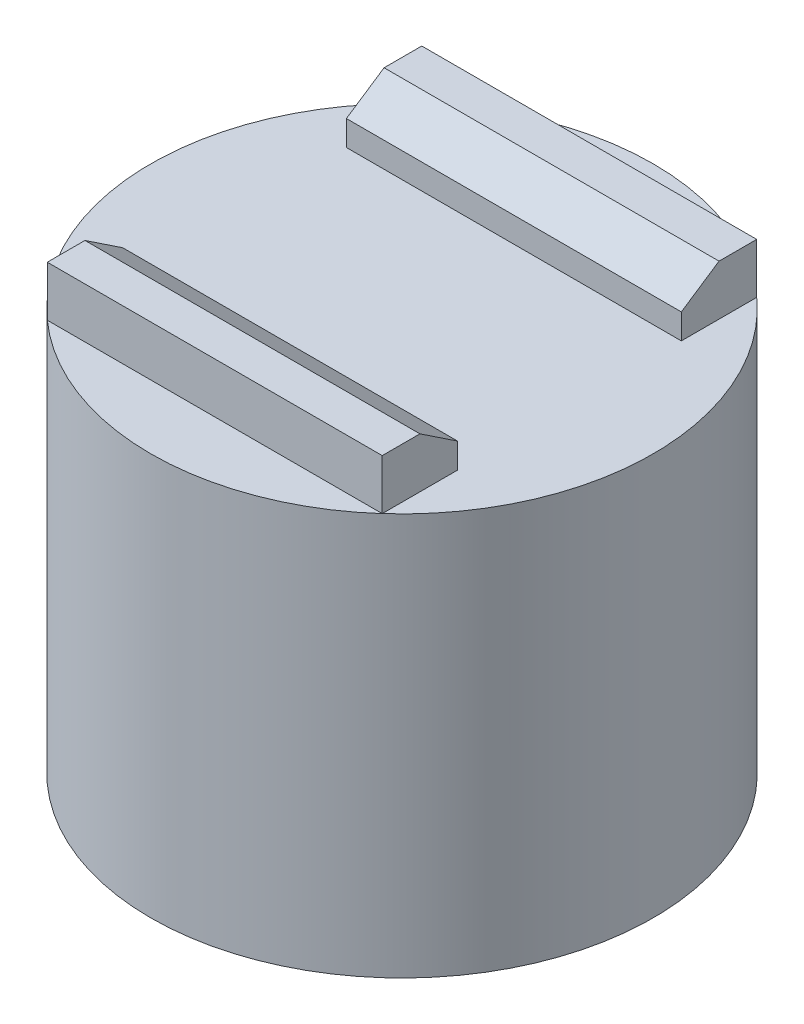
SolidWorks part; units mm, degrees
ref_plane "Front Plane" through (0, 0, 0) normal (0, 0, 1) x (1, 0, 0)
ref_plane "Top Plane" through (0, 0, 0) normal (0, 1, 0) x (1, 0, 0)
ref_plane "Right Plane" through (0, 0, 0) normal (1, 0, 0) x (0, 0, -1)
sketch "Sketch1" plane through (0, 0, 0) normal (0, 1, 0) x (1, 0, 0)
  circle A0 centre (0, 0) radius 15
  dimension "D1" = 30
extrude "Boss-Extrude1" add sketch "Sketch1" along normal blind 24
sketch "Sketch2" plane through (0, 24, 0) normal (0, 1, 0) x (1, 0, 0)
  line L0 (-21.4304, 0) -> (21.9876, 0) construction
  line L1 (-10, 11.1803) -> (10, 11.1803)
  line L2 (-10, 11.1803) -> (-10, 6.6803)
  line L3 (-10, 6.6803) -> (10, 6.6803)
  line L4 (10, 11.1803) -> (10, 6.6803)
  circle A0 centre (0, 0) radius 15 construction
  dimension "D1" = 4.5
  dimension "D2" = 20
extrude "Boss-Extrude2" add sketch "Sketch2" along normal blind 3 contours L1 L4 L3 L2
sketch "Sketch3" plane through (10, 0, 0) normal (1, 0, 0) x (0, 0, -1)
  line L0 (6.6803, 25.5) -> (8.9303, 27)
  line L1 (6.6803, 27) -> (6.6803, 24) construction
  line L2 (11.1803, 27) -> (6.6803, 27) construction
  line L3 (8.9303, 27) -> (6.6803, 27)
  line L4 (6.6803, 27) -> (6.6803, 25.5)
extrude "Cut-Extrude1" cut sketch "Sketch3" against normal blind 43
mirror "Mirror1" about plane through (0, 0, 0) normal (0, 0, 1) of bodies 108
sketch "Sketch4" plane through (0, 0, 0) normal (0, -1, 0) x (1, 0, 0)
  circle A0 centre (0, 0) radius 2.5
  dimension "D1" = 5
extrude "Cut-Extrude2" cut sketch "Sketch4" against normal blind 7
